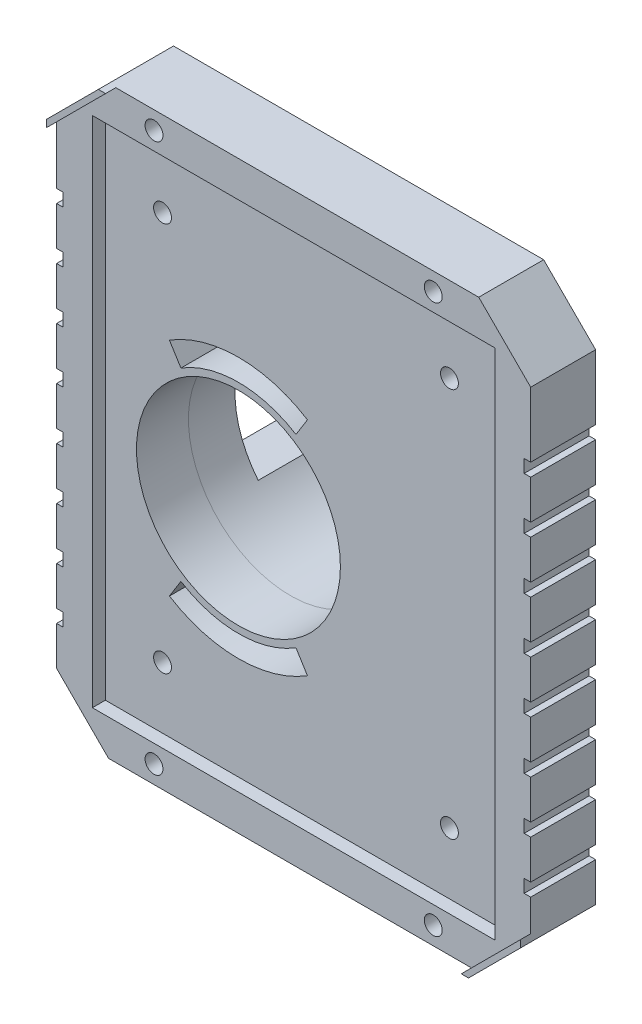
SolidWorks part; units mm, degrees
ref_plane "Front Plane" through (0, 0, 0) normal (0, 0, 1) x (1, 0, 0)
ref_plane "Top Plane" through (0, 0, 0) normal (0, 1, 0) x (1, 0, 0)
ref_plane "Right Plane" through (0, 0, 0) normal (1, 0, 0) x (0, 0, -1)
sketch "Sketch1" plane through (0, 0, 0) normal (0, 0, 1) x (1, 0, 0)
  line L1 (-46.355, -57.15) -> (46.355, -57.15)
  line L2 (-46.355, -57.15) -> (-46.355, 57.15)
  line L3 (-46.355, 57.15) -> (46.355, 57.15)
  line L4 (46.355, -57.15) -> (46.355, 57.15)
  line L5 (-46.355, -57.15) -> (46.355, 57.15) construction
  line L6 (-46.355, 57.15) -> (46.355, -57.15) construction
  point P0 (0, 0)
  dimension "D1" = 92.71
  dimension "D2" = 114.3
extrude "Boss-Extrude1" add sketch "Sketch1" along normal blind 12.7
sketch "Sketch2" plane through (0, 0, 12.7) normal (0, 0, 1) x (1, 0, 0)
  line L0 (46.355, 57.15) -> (-46.355, 57.15) construction
  line L1 (-39.355, -50.15) -> (39.355, -50.15)
  line L2 (-39.355, -50.15) -> (-39.355, 50.15)
  line L3 (-39.355, 50.15) -> (39.355, 50.15)
  line L4 (39.355, -50.15) -> (39.355, 50.15)
  line L5 (-39.355, -50.15) -> (39.355, 50.15) construction
  line L6 (-39.355, 50.15) -> (39.355, -50.15) construction
  line L7 (46.355, -57.15) -> (46.355, 57.15) construction
  point P0 (0, 0)
  dimension "D1" = 7
  dimension "D2" = 7
  dimension "D3" = 100.3
  dimension "D4" = 78.71
extrude "Cut-Extrude1" cut sketch "Sketch2" against normal blind 2.54
sketch "Sketch3" plane through (0, 0, 10.16) normal (0, 0, 1) x (1, 0, 0)
  line L1 (-46.355, 57.15) -> (-46.355, -57.15) construction
  line L2 (-46.355, -57.15) -> (46.355, -57.15) construction
  circle A0 centre (-13.335, -4.572) radius 19.939
  dimension "D1" = 39.878
  dimension "D2" = 52.578
  dimension "D3" = 33.02
extrude "Cut-Extrude2" cut sketch "Sketch3" against normal through all
sketch "Sketch4" plane through (0, 0, 0) normal (0, 0, -1) x (-1, 0, 0)
  line L1 (46.355, -57.15) -> (-46.355, -57.15) construction
  line L4 (46.355, 57.15) -> (46.355, -57.15) construction
  circle A0 centre (13.335, -4.572) radius 19.9875
  circle A1 centre (13.335, -4.572) radius 26.9875
  dimension "D1" = 53.975
  dimension "D2" = 7
  dimension "D3" = 52.578
  dimension "D4" = 33.02
extrude "Boss-Extrude2" add sketch "Sketch4" along normal blind 21.844
sketch "Sketch6" plane through (0, 0, -21.844) normal (0, 0, -1) x (-1, 0, 0)
  circle A0 centre (-2.1178, 12.446) radius 1.75
  circle A1 centre (28.7878, -21.59) radius 1.75
  circle A2 centre (28.7878, 12.446) radius 1.75
  circle A3 centre (-2.1178, -21.59) radius 1.75
  circle A4 centre (13.335, -4.572) radius 26.9875 construction
  circle A5 centre (13.335, -4.572) radius 26.9875 construction
  circle A6 centre (13.335, -4.572) radius 19.9875 construction
  dimension "D1" = 3.5
  dimension "D2" = 3.5
  dimension "D3" = 22.987
  dimension "D4" = 22.987
  dimension "D5" = 3.5
  dimension "D6" = 22.987
  dimension "D9" = 3.5
  dimension "D10" = 22.987
extrude "Cut-Extrude3" cut sketch "Sketch6" against normal blind 19.05
sketch "Sketch12" plane through (0, 0, 0) normal (1, 0, 0) x (0, 0, -1)
  line L0 (21.844, -4.572) -> (0, -4.572) construction
  line L3 (21.844, -31.5595) -> (21.844, 22.4155) construction
  line L4 (9.144, 8.128) -> (21.844, 8.128)
  line L5 (9.144, 8.128) -> (9.144, -17.272)
  line L6 (9.144, -17.272) -> (21.844, -17.272)
  line L7 (21.844, 8.128) -> (21.844, -17.272)
  point P0 (9.144, -4.572)
  dimension "D1" = 12.7
  dimension "D2" = 25.4
  dimension "D3" = 0
extrude "Cut-Extrude6" cut sketch "Sketch12" against normal through all
sketch "Sketch13" plane through (0, 0, 0) normal (1, 0, 0) x (0, 0, -1)
  line L0 (9.144, -17.272) -> (21.844, -17.272) construction
  line L3 (21.844, -31.5595) -> (21.844, 22.4155) construction
  line L4 (10.414, 6.223) -> (21.844, 6.223)
  line L5 (10.414, 6.223) -> (10.414, -5.207)
  line L6 (10.414, -5.207) -> (21.844, -5.207)
  line L7 (21.844, 6.223) -> (21.844, -5.207)
  dimension "D1" = 11.43
  dimension "D2" = 12.065
  dimension "D3" = 11.43
extrude "Cut-Extrude7" cut sketch "Sketch13" along normal through all
sketch "Sketch14" plane through (0, 0, 12.7) normal (0, 0, 1) x (1, 0, 0)
  line L0 (46.355, 57.15) -> (-46.355, 57.15) construction
  line L1 (-46.355, 57.15) -> (-46.355, -57.15) construction
  line L2 (46.355, -57.15) -> (46.355, 57.15) construction
  line L3 (-46.355, -57.15) -> (46.355, -57.15) construction
  circle A0 centre (-27.305, 53.65) radius 1.75
  circle A1 centre (27.305, 53.65) radius 1.75
  circle A2 centre (-27.305, -53.65) radius 1.75
  circle A3 centre (27.305, -53.65) radius 1.75
  dimension "D1" = 3.5
  dimension "D2" = 3.5
  dimension "D3" = 19.05
  dimension "D4" = 19.05
  dimension "D5" = 3.5
  dimension "D7" = 19.05
  dimension "D8" = 3.5
  dimension "D9" = 3.5
  dimension "D10" = 3.5
  dimension "D11" = 3.5
  dimension "D12" = 19.05
  dimension "D6" = 3.5
extrude "Cut-Extrude8" cut sketch "Sketch14" against normal through all
sketch "Sketch16" plane through (0, 0, 0) normal (0, 0, -1) x (-1, 0, 0)
  line L1 (-31.75, 51.11) -> (-22.86, 51.11)
  line L2 (-31.75, 51.11) -> (-31.75, 56.19)
  line L3 (-31.75, 56.19) -> (-22.86, 56.19)
  line L4 (-22.86, 51.11) -> (-22.86, 56.19)
  line L5 (-31.75, 51.11) -> (-22.86, 56.19) construction
  line L6 (-31.75, 56.19) -> (-22.86, 51.11) construction
  line L7 (22.86, 51.11) -> (31.75, 51.11)
  line L8 (22.86, 51.11) -> (22.86, 56.19)
  line L9 (22.86, 56.19) -> (31.75, 56.19)
  line L10 (31.75, 51.11) -> (31.75, 56.19)
  line L11 (22.86, 51.11) -> (31.75, 56.19) construction
  line L12 (22.86, 56.19) -> (31.75, 51.11) construction
  line L13 (22.86, -56.19) -> (31.75, -56.19)
  line L14 (22.86, -56.19) -> (22.86, -51.11)
  line L15 (22.86, -51.11) -> (31.75, -51.11)
  line L16 (31.75, -56.19) -> (31.75, -51.11)
  line L17 (22.86, -56.19) -> (31.75, -51.11) construction
  line L18 (22.86, -51.11) -> (31.75, -56.19) construction
  line L19 (-31.75, -56.19) -> (-22.86, -56.19)
  line L20 (-31.75, -56.19) -> (-31.75, -51.11)
  line L21 (-31.75, -51.11) -> (-22.86, -51.11)
  line L22 (-22.86, -56.19) -> (-22.86, -51.11)
  line L23 (-31.75, -56.19) -> (-22.86, -51.11) construction
  line L24 (-31.75, -51.11) -> (-22.86, -56.19) construction
  point P0 (-27.305, 53.65)
  point P6 (27.305, 53.65)
  point P12 (27.305, -53.65)
  point P18 (-27.305, -53.65)
  dimension "D1" = 5.08
  dimension "D2" = 8.89
  dimension "D3" = 8.89
  dimension "D4" = 5.08
  dimension "D5" = 8.89
  dimension "D6" = 5.08
  dimension "D7" = 5.08
  dimension "D8" = 8.89
extrude "Cut-Extrude9" cut sketch "Sketch16" against normal blind 3.81
sketch "Sketch18" plane through (0, 0, 10.16) normal (0, 0, 1) x (1, 0, 0)
  line L0 (39.355, 50.15) -> (-39.355, 50.15) construction
  line L1 (39.355, 50.15) -> (-39.355, 50.15) construction
  line L2 (39.355, -50.15) -> (39.355, 50.15) construction
  line L3 (-39.355, 50.15) -> (-39.355, -50.15) construction
  line L4 (-39.355, 50.15) -> (-39.355, -50.15) construction
  line L5 (-39.355, -50.15) -> (39.355, -50.15) construction
  circle A0 centre (-28.179, 38.0215) radius 1.75
  circle A1 centre (27.925, 38.0215) radius 1.75
  circle A2 centre (-28.179, -38.1485) radius 1.75
  circle A3 centre (27.925, -38.1485) radius 1.75
  dimension "D1" = 3.5
  dimension "D2" = 3.5
  dimension "D3" = 3.5
  dimension "D4" = 3.5
  dimension "D5" = 12.1285
  dimension "D6" = 12.1285
  dimension "D7" = 11.43
  dimension "D8" = 11.176
  dimension "D9" = 11.176
  dimension "D10" = 12.0015
  dimension "D11" = 11.43
  dimension "D12" = 12.0015
extrude "Cut-Extrude11" cut sketch "Sketch18" against normal blind 5.08
sketch "Sketch19" plane through (0, 0, 12.7) normal (0, 0, 1) x (1, 0, 0)
  line L0 (-46.355, 57.15) -> (-46.355, -57.15) construction
  line L1 (-47.625, -39.37) -> (-45.085, -39.37)
  line L2 (-47.625, -39.37) -> (-47.625, -36.83)
  line L3 (-47.625, -36.83) -> (-45.085, -36.83)
  line L4 (-45.085, -39.37) -> (-45.085, -36.83)
  line L5 (-47.625, -39.37) -> (-45.085, -36.83) construction
  line L6 (-47.625, -36.83) -> (-45.085, -39.37) construction
  line L7 (46.355, -57.15) -> (46.355, 57.15) construction
  line L8 (45.085, -39.37) -> (47.625, -39.37)
  line L9 (45.085, -39.37) -> (45.085, -36.83)
  line L10 (45.085, -36.83) -> (47.625, -36.83)
  line L11 (47.625, -39.37) -> (47.625, -36.83)
  line L12 (45.085, -39.37) -> (47.625, -36.83) construction
  line L13 (45.085, -36.83) -> (47.625, -39.37) construction
  line L14 (-47.625, -26.67) -> (-45.085, -26.67)
  line L15 (-47.625, -29.21) -> (-47.625, -26.67)
  line L16 (-45.085, -29.21) -> (-45.085, -26.67)
  line L17 (45.085, -29.21) -> (45.085, -26.67)
  line L18 (45.085, -26.67) -> (47.625, -26.67)
  line L19 (47.625, -29.21) -> (47.625, -26.67)
  line L20 (45.085, -29.21) -> (47.625, -29.21)
  line L21 (-47.625, -29.21) -> (-45.085, -29.21)
  line L22 (-47.625, -16.51) -> (-45.085, -16.51)
  line L23 (-47.625, -19.05) -> (-47.625, -16.51)
  line L24 (-45.085, -19.05) -> (-45.085, -16.51)
  line L25 (45.085, -19.05) -> (45.085, -16.51)
  line L26 (45.085, -16.51) -> (47.625, -16.51)
  line L27 (47.625, -19.05) -> (47.625, -16.51)
  line L28 (45.085, -19.05) -> (47.625, -19.05)
  line L29 (-47.625, -19.05) -> (-45.085, -19.05)
  line L30 (-47.625, -6.35) -> (-45.085, -6.35)
  line L31 (-47.625, -8.89) -> (-47.625, -6.35)
  line L32 (-45.085, -8.89) -> (-45.085, -6.35)
  line L33 (45.085, -8.89) -> (45.085, -6.35)
  line L34 (45.085, -6.35) -> (47.625, -6.35)
  line L35 (47.625, -8.89) -> (47.625, -6.35)
  line L36 (45.085, -8.89) -> (47.625, -8.89)
  line L37 (-47.625, -8.89) -> (-45.085, -8.89)
  line L38 (-47.625, 3.81) -> (-45.085, 3.81)
  line L39 (-47.625, 1.27) -> (-47.625, 3.81)
  line L40 (-45.085, 1.27) -> (-45.085, 3.81)
  line L41 (45.085, 1.27) -> (45.085, 3.81)
  line L42 (45.085, 3.81) -> (47.625, 3.81)
  line L43 (47.625, 1.27) -> (47.625, 3.81)
  line L44 (45.085, 1.27) -> (47.625, 1.27)
  line L45 (-47.625, 1.27) -> (-45.085, 1.27)
  line L46 (-47.625, 13.97) -> (-45.085, 13.97)
  line L47 (-47.625, 11.43) -> (-47.625, 13.97)
  line L48 (-45.085, 11.43) -> (-45.085, 13.97)
  line L49 (45.085, 11.43) -> (45.085, 13.97)
  line L50 (45.085, 13.97) -> (47.625, 13.97)
  line L51 (47.625, 11.43) -> (47.625, 13.97)
  line L52 (45.085, 11.43) -> (47.625, 11.43)
  line L53 (-47.625, 11.43) -> (-45.085, 11.43)
  line L54 (-47.625, 24.13) -> (-45.085, 24.13)
  line L55 (-47.625, 21.59) -> (-47.625, 24.13)
  line L56 (-45.085, 21.59) -> (-45.085, 24.13)
  line L57 (45.085, 21.59) -> (45.085, 24.13)
  line L58 (45.085, 24.13) -> (47.625, 24.13)
  line L59 (47.625, 21.59) -> (47.625, 24.13)
  line L60 (45.085, 21.59) -> (47.625, 21.59)
  line L61 (-47.625, 21.59) -> (-45.085, 21.59)
  line L62 (-47.625, 34.29) -> (-45.085, 34.29)
  line L63 (-47.625, 31.75) -> (-47.625, 34.29)
  line L64 (-47.625, 31.75) -> (-45.085, 31.75)
  line L65 (-45.085, 31.75) -> (-45.085, 34.29)
  line L66 (47.625, 31.75) -> (47.625, 34.29)
  line L67 (45.085, 34.29) -> (47.625, 34.29)
  line L68 (45.085, 31.75) -> (45.085, 34.29)
  line L69 (45.085, 31.75) -> (47.625, 31.75)
  point P0 (-46.355, -38.1)
  point P7 (46.355, -38.1)
  dimension "D1" = 2.54
  dimension "D2" = 2.54
  dimension "D3" = 17.78
  dimension "D4" = 2.54
  dimension "D5" = 2.54
  dimension "D6" = 17.78
  dimension "D7" = 7
  dimension "D8" = 2
extrude "Cut-Extrude12" cut sketch "Sketch19" against normal through all
chamfer "Chamfer2" distance 10.16 angle 45 4 edges at (-46.355, -57.15, 6.35) (46.355, -57.15, 6.35) (46.355, 57.15, 6.35) (-46.355, 57.15, 6.35)
sketch "Sketch20" plane through (0, 0, -21.844) normal (0, 0, -1) x (-1, 0, 0)
  line L5 (-0.1618, 17.0996) -> (2.0848, 13.4922)
  line L6 (24.5852, 13.4922) -> (26.8318, 17.0996)
  line L7 (2.0848, -22.6362) -> (-0.1618, -26.2436)
  line L8 (24.5852, -22.6362) -> (26.8318, -26.2436)
  circle A1 centre (13.335, -4.572) radius 19.9875 construction
  arc A10 (2.0848, -22.6362) -> (24.5852, -22.6362) centre (13.335, -4.572) ccw
  arc A11 (-0.1618, -26.2436) -> (26.8318, -26.2436) centre (13.335, -4.572) ccw
  arc A12 (28.7691, 8.128) -> (-3.4867, 6.223) centre (13.335, -4.572) ccw construction
  circle A13 centre (-2.1178, 12.446) radius 1.75 construction
  circle A14 centre (28.7878, 12.446) radius 1.75 construction
  circle A15 centre (-2.1178, -21.59) radius 1.75 construction
  arc A16 (24.5852, 13.4922) -> (2.0848, 13.4922) centre (13.335, -4.572) ccw
  arc A17 (26.8318, 17.0996) -> (-0.1618, 17.0996) centre (13.335, -4.572) ccw
  dimension "D1" = 1.2935
  dimension "D2" = 5.5433
  dimension "D5" = 4.1205
  dimension "D3" = 4.1205
  dimension "D4" = 4.1205
extrude "Cut-Extrude13" cut sketch "Sketch20" against normal through all
sketch "Sketch21" plane through (0, 0, 12.7) normal (0, 0, 1) x (1, 0, 0)
  line L2 (-40.5679, 51.3629) -> (-46.355, 45.5758)
  line L3 (-46.355, 46.99) -> (-46.355, 34.29) construction
  line L4 (-46.355, 45.5758) -> (-46.355, 46.99)
  line L5 (-46.355, 46.99) -> (-36.195, 57.15)
  line L6 (-40.5679, 51.3629) -> (-34.7808, 57.15)
  line L7 (36.195, 57.15) -> (-36.195, 57.15) construction
  line L8 (-34.7808, 57.15) -> (-36.195, 57.15)
  line L10 (40.5679, -51.3629) -> (34.7808, -57.15)
  line L11 (-36.195, -57.15) -> (36.195, -57.15) construction
  line L12 (34.7808, -57.15) -> (36.195, -57.15)
  line L13 (36.195, -57.15) -> (46.355, -46.99)
  line L14 (40.5679, -51.3629) -> (46.355, -45.5758)
  line L15 (46.355, -46.99) -> (46.355, -39.37) construction
  line L16 (46.355, -45.5758) -> (46.355, -46.99)
extrude "Boss-Extrude3" add sketch "Sketch21" along normal blind 2
sketch "Sketch22" plane through (0, 0, -21.844) normal (0, 0, -1) x (-1, 0, 0)
  line L0 (31.7878, 8.128) -> (31.7878, 13.716)
  line L1 (37.1475, 8.128) -> (28.7691, 8.128) construction
  line L2 (31.7878, 8.128) -> (37.1475, 8.128)
  line L3 (31.7878, 13.716) -> (33.1813, 13.716)
  circle A0 centre (28.7878, 12.446) radius 1.75 construction
  arc A1 (37.1475, 8.128) -> (-11.3995, 6.223) centre (13.335, -4.572) ccw construction
  arc A4 (37.1475, 8.128) -> (33.1813, 13.716) centre (13.335, -4.572) ccw
  dimension "D3" = 1.27
  dimension "D1" = 5.588
  dimension "D2" = 3
extrude "Cut-Extrude14" cut sketch "Sketch22" against normal blind 7.62
